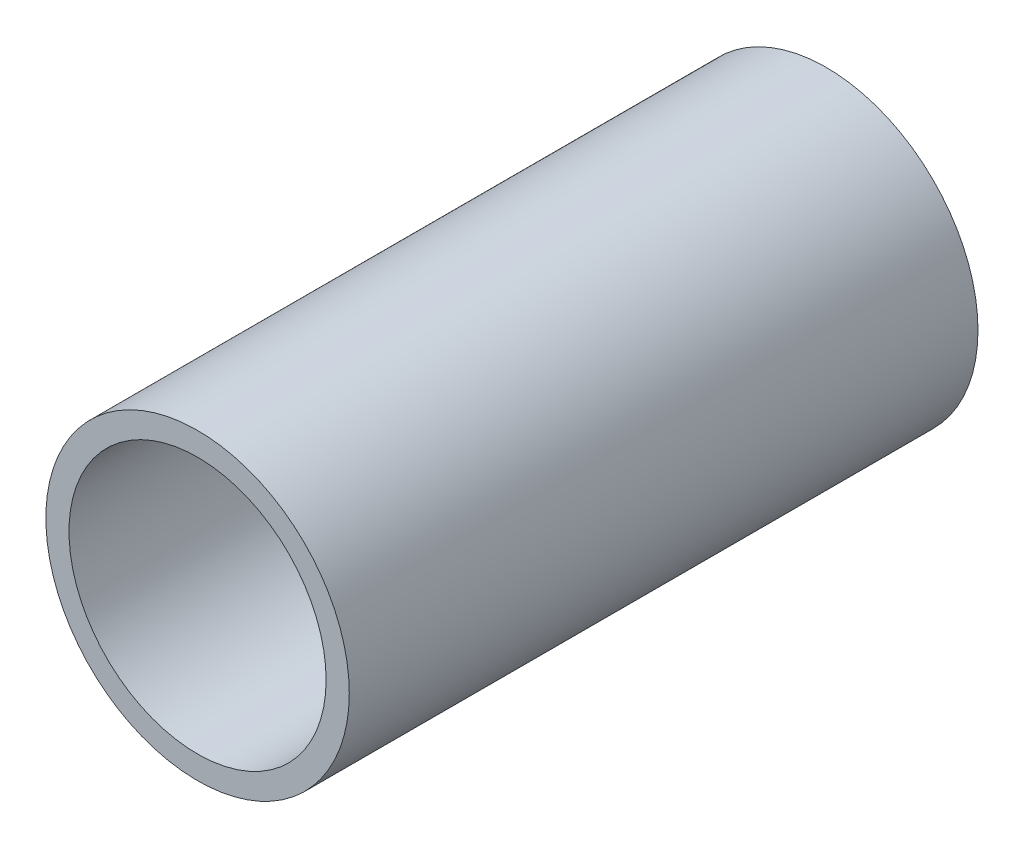
SolidWorks part; units mm, degrees
ref_plane "Alzado" through (0, 0, 0) normal (0, 0, 1) x (1, 0, 0)
ref_plane "Planta" through (0, 0, 0) normal (0, 1, 0) x (1, 0, 0)
ref_plane "Vista lateral" through (0, 0, 0) normal (1, 0, 0) x (0, 0, -1)
sketch "Croquis2" plane through (0, 0, 0) normal (0, 0, 1) x (1, 0, 0)
  circle A0 centre (0, 0) radius 24.13
  circle A1 centre (0, 0) radius 20.447
  dimension "D1" = 48.26
  dimension "D2" = 40.894
extrude "Saliente-Extruir1" add sketch "Croquis2" along normal mid plane 100
